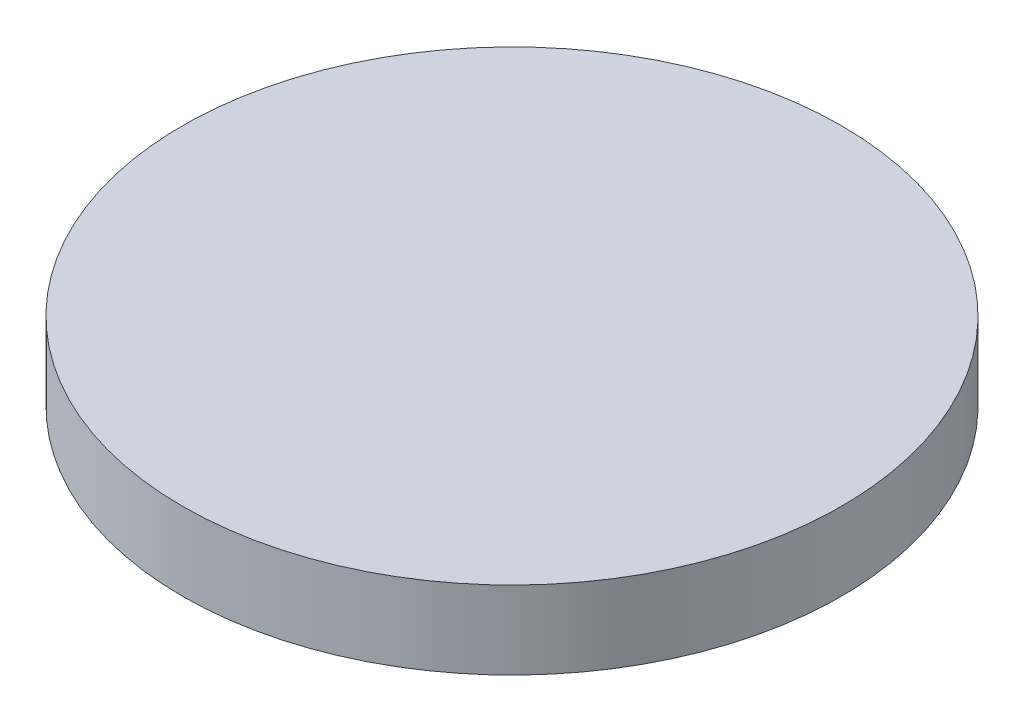
SolidWorks part; units mm, degrees
material "Сталь 3 ГОСТ 535-88"
ref_plane "Спереди" through (0, 0, 0) normal (0, 0, 1) x (1, 0, 0)
ref_plane "Сверху" through (0, 0, 0) normal (0, 1, 0) x (1, 0, 0)
ref_plane "Справа" through (0, 0, 0) normal (1, 0, 0) x (0, 0, -1)
sketch "Эскиз1" plane through (0, 0, 0) normal (0, 1, 0) x (1, 0, 0)
  circle A0 centre (0, 0) radius 46.5
  dimension "D1" = 93
extrude "Бобышка-Вытянуть1" add sketch "Эскиз1" along normal blind 6
sketch "Эскиз2" plane through (0, 0, 0) normal (0, -1, 0) x (1, 0, 0)
  circle A0 centre (0, 0) radius 46.5 construction
  circle A1 centre (0, 0) radius 46.5
  circle A2 centre (0, 0) radius 41.5
  dimension "D1" = 5
extrude "Бобышка-Вытянуть2" add sketch "Эскиз2" along normal blind 5
